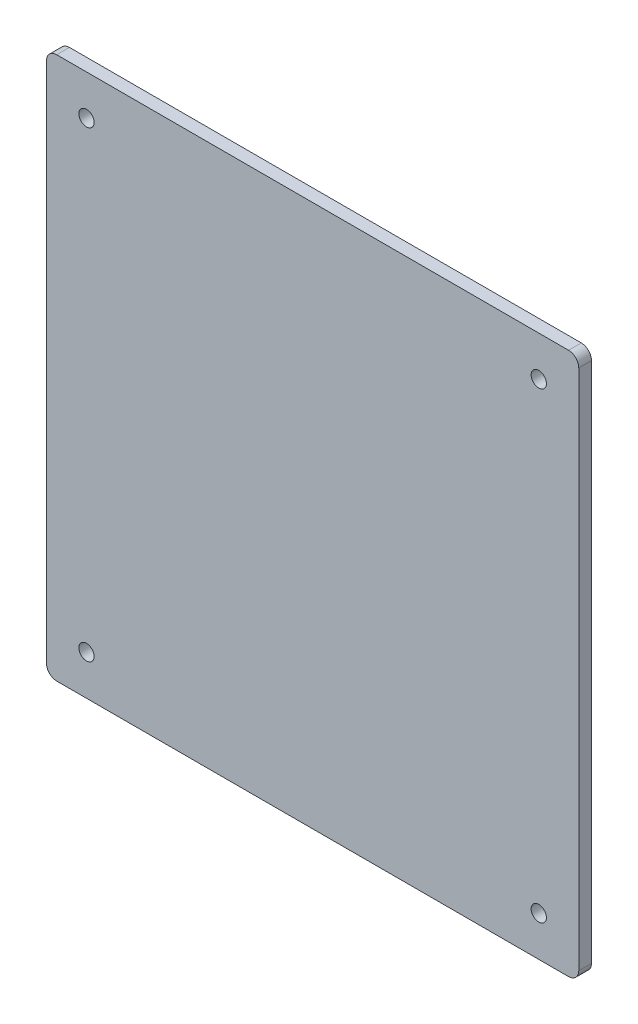
SolidWorks part; units mm, degrees
ref_plane "Front Plane" through (0, 0, 0) normal (0, 0, 1) x (1, 0, 0)
ref_plane "Top Plane" through (0, 0, 0) normal (0, 1, 0) x (1, 0, 0)
ref_plane "Right Plane" through (0, 0, 0) normal (1, 0, 0) x (0, 0, -1)
sketch "Sketch1" plane through (0, 0, 0) normal (0, 0, 1) x (1, 0, 0)
  line L1 (0, 0) -> (132.715, 0)
  line L2 (0, 0) -> (0, 135.255)
  line L3 (0, 135.255) -> (132.715, 135.255)
  line L4 (132.715, 0) -> (132.715, 135.255)
  dimension "D1" = 132.715
  dimension "D2" = 135.255
extrude "Boss-Extrude1" add sketch "Sketch1" along normal blind 3.175
sketch "Sketch4" plane through (0, 0, 3.175) normal (0, 0, 1) x (1, 0, 0)
  line L0 (0, 135.255) -> (132.715, 0) construction
  line L2 (9.9695, 9.9695) -> (122.7455, 9.9695) construction
  line L3 (9.9695, 9.9695) -> (9.9695, 125.2855) construction
  line L4 (9.9695, 125.2855) -> (122.7455, 125.2855) construction
  line L5 (122.7455, 9.9695) -> (122.7455, 125.2855) construction
  line L6 (9.9695, 9.9695) -> (122.7455, 125.2855) construction
  line L7 (9.9695, 125.2855) -> (122.7455, 9.9695) construction
  circle A0 centre (9.9695, 125.2855) radius 1.905
  circle A2 centre (122.7455, 9.9695) radius 1.905
  circle A3 centre (9.9695, 9.9695) radius 1.905
  circle A4 centre (122.7455, 125.2855) radius 1.905
  point P4 (66.3575, 67.6275)
  point P11 (123.825, 8.255)
  dimension "D3" = 3.81
  dimension "D1" = 115.316
  dimension "D2" = 112.776
extrude "Cut-Extrude1" cut sketch "Sketch4" against normal blind 3.175
fillet "Fillet1" radius 2.54 4 edges at (0, 135.255, 1.5875) (0, 0, 1.5875) (132.715, 0, 1.5875) (132.715, 135.255, 1.5875)
equation "\"bHeight\" = 4.95"
equation "\"bWidth\" = 4.85"
equation "\"D2@Sketch1\"=\"bHeight\"+(3/8)"
equation "\"D1@Sketch1\"=\"bWidth\"+(3/8)"
equation "\"hHeight\" =4.54"
equation "\"hWidth\"= 4.44"
equation "\"D1@Sketch4\"=\"hHeight\""
equation "\"D2@Sketch4\"=\"hWidth\""
equation "\"hD\" = .16"
equation "\"hR\"= .08"
